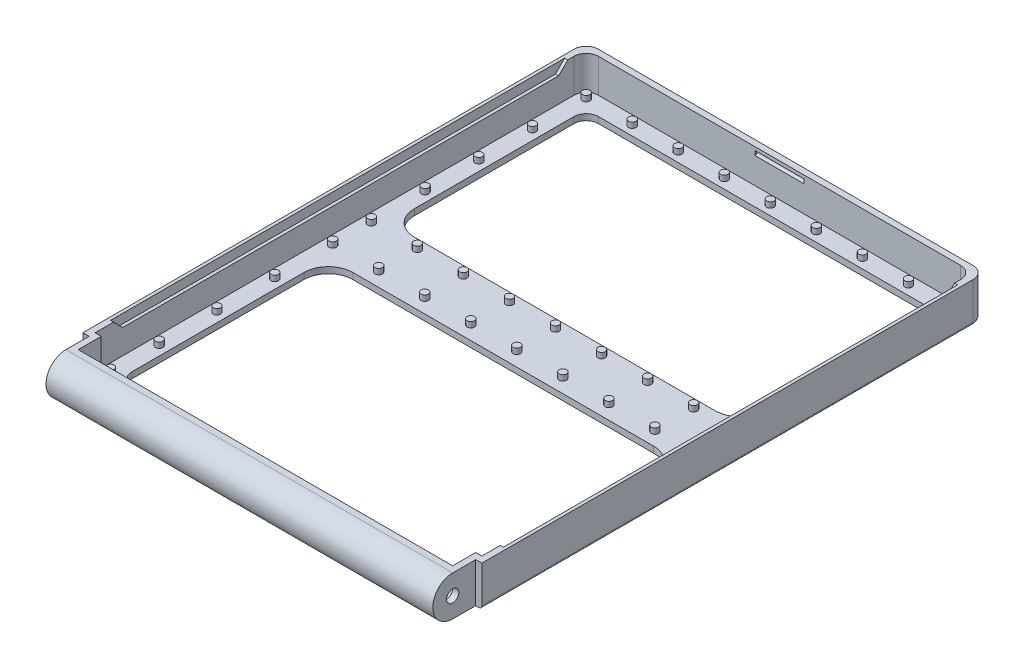
SolidWorks part; units mm, degrees
ref_plane "Alzado" through (0, 0, 0) normal (0, 0, 1) x (1, 0, 0)
ref_plane "Planta" through (0, 0, 0) normal (0, 1, 0) x (1, 0, 0)
ref_plane "Vista lateral" through (0, 0, 0) normal (1, 0, 0) x (0, 0, -1)
sketch "Croquis1" plane through (0, 0, 0) normal (0, 1, 0) x (1, 0, 0)
  line L0 (130, 0) -> (128, 0)
  line L1 (0, 0) -> (2, 0)
  line L2 (0, 0) -> (0, 160)
  line L3 (4, 164) -> (126, 164)
  line L4 (130, 0) -> (130, 160)
  line L5 (128, 0) -> (128, -14)
  line L6 (128, -14) -> (2, -14)
  line L7 (2, -14) -> (2, 0)
  arc A0 (4, 164) -> (0, 160) centre (4, 160) ccw
  arc A1 (126, 164) -> (130, 160) centre (126, 160) cw
extrude "Saliente-Extruir1" add sketch "Croquis1" along normal blind 13
sketch "Croquis7" plane through (0, 13, 0) normal (0, 1, 0) x (1, 0, 0)
  line L0 (2, 0) -> (128, 0)
  line L8 (62.0012, 162) -> (6, 162)
  line L9 (2, 158) -> (2, 2)
  line L10 (2, 2) -> (128, 2)
  line L11 (128, 2) -> (128, 158)
  line L12 (124, 162) -> (62.0012, 162)
  arc A0 (6, 162) -> (2, 158) centre (6, 158) ccw
  arc A1 (124, 162) -> (128, 158) centre (124, 158) cw
extrude "Cortar-Extruir7" cut sketch "Croquis7" against normal blind 11 contours A1 L12 L8 A0 L9 L10 L11
sketch "Croquis8" plane through (128, 0, 0) normal (1, 0, 0) x (0, 0, -1)
  line L0 (-7.5, 28.0923) -> (-7.5, -27.9424)
  line L2 (-14, 13) -> (0, 13) construction
  line L3 (-7.5, 13) -> (-7.5, 0)
  arc A0 (-7.5, 13) -> (-7.5, 0) centre (-7.5, 6.5) ccw
  line M3 (-14, 0) -> (0, 0)
  line M5 (0, 13) -> (-14, 13)
  line M6 (-14, 13) -> (-14, 0)
extrude "Cortar-Extruir9" cut sketch "Croquis8" against normal blind 140 contours A0 M5 M6 | A0 M6 M3
ref_plane "Plano1" through (4, 0, 0) normal (1, 0, 0) x (0, 0, -1)
sketch "Croquis10" plane through (4, 0, 0) normal (1, 0, 0) x (0, 0, -1)
  circle A0 centre (-7.5, 6.5) radius 4.5
extrude "Cortar-Extruir10" cut sketch "Croquis10" along normal blind 122
sketch "Croquis11" plane through (0, 13, 0) normal (0, 1, 0) x (1, 0, 0)
  line L1 (4, -5.5) -> (4, 14.525)
  line L4 (4, -5.5) -> (6, -5.5)
  line L5 (4, -7.15) -> (4, 7.15) construction
  line L6 (126, -5.5) -> (126, 14.525)
  line L9 (126, -5.5) -> (4, -5.5)
  line L10 (126, 14.525) -> (4, 14.525)
  line M4 (128, 2) -> (2, 2)
extrude "Cortar-Extruir12" cut sketch "Croquis11" against normal blind 11 contours L9 L6 L1 L4 M4 | L6 L10 L1 M4
sketch "Croquis12" plane through (4, 0, 0) normal (1, 0, 0) x (0, 0, -1)
  circle A0 centre (-7.5, 6.5) radius 2
extrude "Cortar-Extruir13" cut sketch "Croquis12" against normal blind 130 and the other way blind 130
fillet "Redondeo1" radius 1 5 edges at (130, 0, -80) (128.8284, 0, -162.8284) (65, 0, -164) (1.1716, 0, -162.8284) (0, 0, -80)
ref_plane "Plano2" through (2, 0, 0) normal (1, 0, 0) x (0, 0, -1)
ref_plane "Plano3" through (128, 0, 0) normal (1, 0, 0) x (0, 0, -1)
sketch "Croquis17" plane through (2, 0, 0) normal (1, 0, 0) x (0, 0, -1)
  line L1 (153, 10) -> (11, 10)
  line L3 (8, 13) -> (156, 13)
  line L4 (156, 13) -> (153, 10)
  line L5 (8, 13) -> (11, 10)
extrude "Cortar-Extruir14" cut sketch "Croquis17" against normal blind 1
sketch "Croquis19" plane through (128, 0, 0) normal (1, 0, 0) x (0, 0, -1)
  line L1 (11, 10) -> (153, 10)
  line L3 (156, 13) -> (8, 13)
  line L4 (8, 13) -> (11, 10)
  line L5 (156, 13) -> (153, 10)
extrude "Cortar-Extruir15" cut sketch "Croquis19" along normal blind 1
sketch "Croquis20" plane through (0, 0, 0) normal (0, -1, 0) x (1, 0, 0)
  line L0 (85, -72) -> (114, -72)
  line L1 (45, -92) -> (85, -92)
  line L3 (85, -72) -> (45, -72)
  line L4 (8, -100) -> (8, -152)
  line L5 (85, -92) -> (114, -92)
  line L6 (45, -72) -> (16, -72)
  line L7 (45, -92) -> (16, -92)
  line L11 (118, -4) -> (12, -4)
  line L13 (126, -91.0232) -> (126, -92)
  line L18 (122, -100) -> (122, -152)
  line L19 (122, -24.16) -> (122, -64)
  line L21 (122, -24.16) -> (122, -8)
  line L24 (8, -8) -> (8, -64)
  line L26 (68.2817, -156) -> (118, -156)
  line L27 (68.2817, -156) -> (12, -156)
  line L28 (59.9773, -156) -> (59.9773, -152)
  arc A0 (16, -92) -> (8, -100) centre (16, -100) ccw
  arc A1 (114, -92) -> (122, -100) centre (114, -100) cw
  arc A2 (16, -72) -> (8, -64) centre (16, -64) cw
  arc A3 (122, -64) -> (114, -72) centre (114, -64) cw
  arc A4 (122, -152) -> (118, -156) centre (118, -152) cw
  arc A5 (12, -156) -> (8, -152) centre (12, -152) cw
  arc A6 (12, -4) -> (8, -8) centre (12, -8) ccw
  arc A7 (122, -8) -> (118, -4) centre (118, -8) ccw
  point P2 (65, -82)
extrude "Cortar-Extruir17" cut sketch "Croquis20" against normal blind 4
sketch "Croquis21" plane through (0, 0, 0) normal (0, -1, 0) x (1, 0, 0)
  ellipse E0 centre (64.5555, -81.6566) end of major axis (29.5555, -81.6566) minor radius 8
extrude "Cortar-Extruir19" cut sketch "Croquis21" against normal blind 0.4
sketch "Croquis22" plane through (0, 2, 0) normal (0, 1, 0) x (1, 0, 0)
  circle A0 centre (20, 159) radius 1.2
  circle A1 centre (35, 159) radius 1.2
  circle A2 centre (50, 159) radius 1.2
  circle A3 centre (65, 159) radius 1.2
  circle A4 centre (80, 159) radius 1.2
  circle A5 centre (95, 159) radius 1.2
  circle A6 centre (110, 159) radius 1.2
  circle A7 centre (125, 159) radius 1.2
  circle A8 centre (5, 159) radius 1.2
  circle A9 centre (5, 89) radius 1.2
  circle A10 centre (20, 89) radius 1.2
  circle A11 centre (35, 89) radius 1.2
  circle A12 centre (50, 89) radius 1.2
  circle A13 centre (65, 89) radius 1.2
  circle A14 centre (80, 89) radius 1.2
  circle A15 centre (95, 89) radius 1.2
  circle A16 centre (110, 89) radius 1.2
  circle A17 centre (125, 89) radius 1.2
  circle A18 centre (125, 76.3962) radius 1.2
  circle A19 centre (110, 76.3962) radius 1.2
  circle A20 centre (80, 76.3962) radius 1.2
  circle A21 centre (65, 76.3962) radius 1.2
  circle A22 centre (95, 76.3962) radius 1.2
  circle A23 centre (50, 76.3962) radius 1.2
  circle A24 centre (20, 76.3962) radius 1.2
  circle A25 centre (35, 76.3962) radius 1.2
  circle A26 centre (5, 76.3962) radius 1.2
  circle A27 centre (20, 1) radius 1.2
  circle A28 centre (35, 1) radius 1.2
  circle A29 centre (50, 1) radius 1.2
  circle A30 centre (65, 1) radius 1.2
  circle A31 centre (80, 1) radius 1.2
  circle A32 centre (95, 1) radius 1.2
  circle A33 centre (110, 1) radius 1.2
  circle A34 centre (5, 38.6981) radius 1.2
  circle A35 centre (125, 38.6981) radius 1.2
  circle A36 centre (5, 57.5472) radius 1.2
  circle A37 centre (125, 57.5472) radius 1.2
  circle A38 centre (5, 19.8491) radius 1.2
  circle A39 centre (125, 19.8491) radius 1.2
  circle A40 centre (125, 4) radius 1.2
  circle A41 centre (5, 4) radius 1.2
  circle A42 centre (125, 141.5) radius 1.2
  circle A43 centre (125, 124) radius 1.2
  circle A44 centre (125, 106.5) radius 1.2
  circle A45 centre (5, 141.5) radius 1.2
  circle A46 centre (5, 124) radius 1.2
  circle A47 centre (5, 106.5) radius 1.2
extrude "Saliente-Extruir3" add sketch "Croquis22" along normal blind 1.8
ref_plane "Plano5" through (73, 0, 0) normal (1, 0, 0) x (0, 0, -1)
sketch "Croquis25" plane through (73, 0, 0) normal (1, 0, 0) x (0, 0, -1)
  line L4 (162, 13) -> (162, 10.5) construction
  circle A0 centre (162, 11.2) radius 0.7
extrude "Cortar-Extruir20" cut sketch "Croquis25" against normal blind 16
